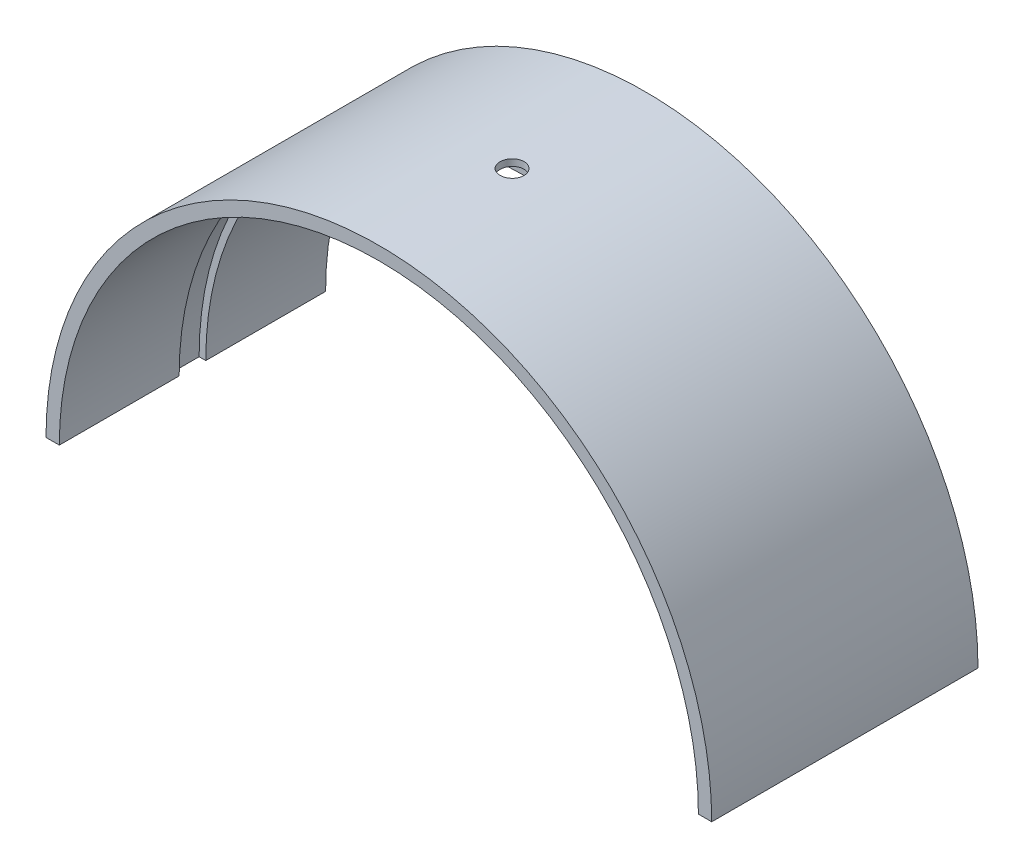
SolidWorks part; units mm, degrees
ref_plane "Front Plane" through (0, 0, 0) normal (0, 0, 1) x (1, 0, 0)
ref_plane "Top Plane" through (0, 0, 0) normal (0, 1, 0) x (1, 0, 0)
ref_plane "Right Plane" through (0, 0, 0) normal (1, 0, 0) x (0, 0, -1)
sketch "Sketch1" plane through (0, 0, 0) normal (0, 0, 1) x (1, 0, 0)
  line L0 (25, 0) -> (24, 0)
  line L1 (-24, 0) -> (-25, 0)
  arc A0 (25, 0) -> (-25, 0) centre (0, 0) ccw
  arc A1 (24, 0) -> (-24, 0) centre (0, 0) ccw
  circle A2 centre (0, 0) radius 25 construction
  circle A3 centre (0, 0) radius 24 construction
  dimension "D1" = 50
  dimension "D2" = 1
extrude "Boss-Extrude1" add sketch "Sketch1" along normal blind 20
sketch "Sketch2" plane through (0, 0, 0) normal (0, -1, 0) x (1, 0, 0)
  line L0 (-24, 20) -> (-24, 0) construction
  line L1 (-24, 9) -> (-24.5, 9)
  line L2 (-24, 9) -> (-24, 11)
  line L3 (-24, 11) -> (-24.5, 11)
  line L4 (-24.5, 9) -> (-24.5, 11)
  line L5 (0, 0) -> (0, 7.0049) construction
  point P6 (-24, 10)
  dimension "D1" = 2
  dimension "D2" = 0.5
  dimension "D3" = 10
revolve "Cut-Revolve1" cut sketch "Sketch2" angle 360 about L5
sketch "Sketch3" plane through (0, 0, 0) normal (0, -1, 0) x (1, 0, 0)
  line L0 (-24.5, 10) -> (0, 10) construction
  line L1 (-24.5, 11) -> (-24.5, 9) construction
  circle A0 centre (0, 10) radius 0.9
  dimension "D1" = 1.8
  dimension "D2" = 10
extrude "Cut-Extrude1" cut sketch "Sketch3" against normal through all
